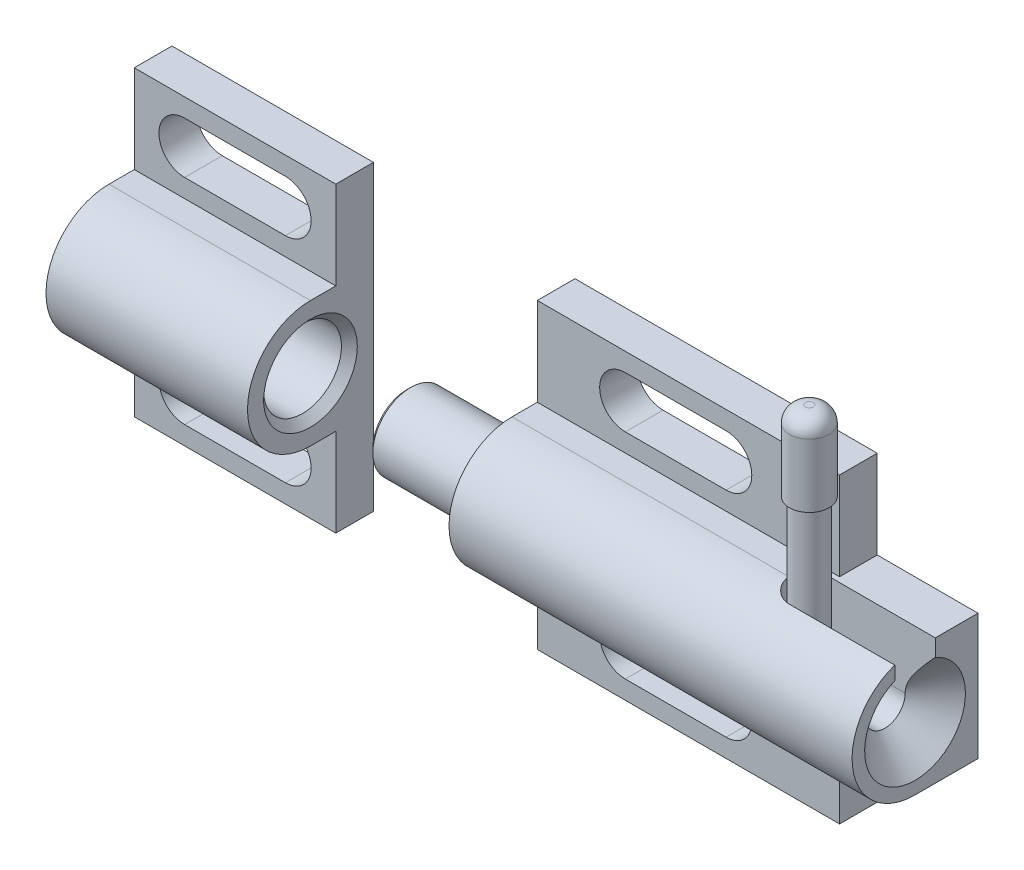
SolidWorks part; units mm, degrees
ref_plane "Front Plane" through (0, 0, 0) normal (0, 0, 1) x (1, 0, 0)
ref_plane "Top Plane" through (0, 0, 0) normal (0, 1, 0) x (1, 0, 0)
ref_plane "Right Plane" through (0, 0, 0) normal (1, 0, 0) x (0, 0, -1)
sketch "Sketch1" plane through (0, 0, 0) normal (1, 0, 0) x (0, 0, -1)
  line L0 (0, -19.05) -> (0, 19.05)
  line L3 (-4.7498, -19.05) -> (-4.7498, -7.9375)
  line L4 (-4.7498, 19.05) -> (0, 19.05)
  line L5 (0, -19.05) -> (-4.7498, -19.05)
  line L16 (-4.7498, 7.9375) -> (-4.7498, 19.05)
  line L17 (0, 0) -> (-15.875, 0) construction
  line L18 (-7.9375, 7.9375) -> (-4.7498, 7.9375)
  line L19 (-7.9375, -7.9375) -> (-4.7498, -7.9375)
  arc A10 (-7.9375, 7.9375) -> (-7.9375, -7.9375) centre (-7.9375, 0) ccw
  circle A12 centre (-7.9375, 0) radius 7.9375 construction
  dimension "D1" = 38.1
  dimension "D2" = 15.875
  dimension "D3" = 4.7498
extrude "Boss-Extrude1" add sketch "Sketch1" against normal blind 25.4
sketch "Sketch2" plane through (0, 0, 0) normal (0, 1, 0) x (1, 0, 0)
  line L0 (0, -7.9375) -> (-25.4, -7.9375) construction
  line L1 (-25.4, -7.9375) -> (-25.4, -15.875) construction
  line L2 (-25.4, -7.9375) -> (-25.4, -10.4902)
  line L3 (-25.4, -10.4902) -> (-19.05, -10.4902)
  line L4 (-19.05, -10.4902) -> (-19.05, -12.8397)
  line L5 (-19.05, -12.8397) -> (-1, -12.8397)
  line L6 (-1, -12.8397) -> (0, -13.8397)
  line L7 (0, -13.8397) -> (0, -7.9375)
  line L8 (0, -7.9375) -> (-25.4, -7.9375)
  dimension "D1" = 5.1054
  dimension "D2" = 9.8044
  dimension "D3" = 19.05
  dimension "D4" = 1
  dimension "D5" = 45
revolve "Cut-Revolve1" cut sketch "Sketch2" angle 360 about L0
sketch "Sketch3" plane through (0, 0, 0) normal (0, 0, 1) x (1, 0, 0)
  line L0 (-19.05, 13.4874) -> (-6.35, 13.4874) construction
  line L1 (-19.05, 16.7259) -> (-6.35, 16.7259)
  line L2 (-19.05, 10.2489) -> (-6.35, 10.2489)
  line L3 (-25.4, 0) -> (0, 0) construction
  line L4 (-25.4, -19.05) -> (-25.4, 19.05) construction
  line L5 (-19.05, -13.4874) -> (-6.35, -13.4874) construction
  line L6 (-19.05, -16.7259) -> (-6.35, -16.7259)
  line L7 (-19.05, -10.2489) -> (-6.35, -10.2489)
  line L8 (-12.7, 13.4874) -> (-12.7, 0) construction
  arc A0 (-19.05, 16.7259) -> (-19.05, 10.2489) centre (-19.05, 13.4874) ccw
  arc A1 (-6.35, 10.2489) -> (-6.35, 16.7259) centre (-6.35, 13.4874) ccw
  arc A2 (-19.05, -16.7259) -> (-19.05, -10.2489) centre (-19.05, -13.4874) cw
  arc A3 (-6.35, -10.2489) -> (-6.35, -16.7259) centre (-6.35, -13.4874) cw
  point P2 (-12.7, 13.4874)
  point P14 (-12.7, -13.4874)
  dimension "D1" = 26.9748
  dimension "D2" = 6.477
  dimension "D3" = 12.7
extrude "Cut-Extrude2" cut sketch "Sketch3" along normal up to next
ref_plane "Plane1" through (25.4, 0, 0) normal (1, 0, 0) x (0, 0, -1)
sketch "Sketch4" plane through (25.4, 0, 0) normal (1, 0, 0) x (0, 0, -1)
  line L7 (0, -19.05) -> (0, 19.05)
  line L8 (0, 19.05) -> (-4.7498, 19.05)
  line L9 (-4.7498, 19.05) -> (-4.7498, 7.9375)
  line L10 (-4.7498, 7.9375) -> (-7.9375, 7.9375)
  line L11 (-7.9375, -7.9375) -> (-4.7498, -7.9375)
  line L12 (-4.7498, -7.9375) -> (-4.7498, -19.05)
  line L13 (-4.7498, -19.05) -> (0, -19.05)
  line L14 (0, -19.05) -> (0, 19.05)
  line L15 (0, 19.05) -> (-4.7498, 19.05)
  line L16 (-4.7498, 19.05) -> (-4.7498, 7.9375)
  line L17 (-4.7498, 7.9375) -> (-7.9375, 7.9375)
  line L18 (-7.9375, -7.9375) -> (-4.7498, -7.9375)
  line L19 (-4.7498, -7.9375) -> (-4.7498, -19.05)
  line L20 (-4.7498, -19.05) -> (0, -19.05)
  arc A1 (-7.9375, 7.9375) -> (-7.9375, -7.9375) centre (-7.9375, 0) ccw
  arc A2 (-7.9375, 7.9375) -> (-7.9375, -7.9375) centre (-7.9375, 0) ccw
  dimension "D1" = 0
extrude "Boss-Extrude2" add sketch "Sketch4" along normal blind 50.8 separate body
sketch "Sketch5" plane through (76.2, 0, 0) normal (1, 0, 0) x (0, 0, -1)
  line L1 (0, 19.05) -> (-4.7498, 19.05)
  line L2 (0, 19.05) -> (0, 7.9375)
  line L3 (0, 7.9375) -> (-4.7498, 7.9375)
  line L4 (-4.7498, 19.05) -> (-4.7498, 7.9375)
  line L5 (0, -19.05) -> (-4.7498, -19.05)
  line L6 (0, -19.05) -> (0, -7.9375)
  line L7 (0, -7.9375) -> (-4.7498, -7.9375)
  line L8 (-4.7498, -19.05) -> (-4.7498, -7.9375)
extrude "Cut-Extrude3" cut sketch "Sketch5" against normal blind 12.7
sketch "Sketch6" plane through (0, 0, 0) normal (0, 1, 0) x (1, 0, 0)
  line L0 (25.4, -7.9375) -> (76.2, -7.9375) construction
  line L1 (76.2, -15.875) -> (76.2, -7.9375) construction
  line L2 (25.4, -7.9375) -> (25.4, -13.8397)
  line L3 (25.4, -7.9375) -> (25.4, -15.875) construction
  line L4 (25.4, -13.8397) -> (26.4, -12.8397)
  line L5 (26.4, -12.8397) -> (57.15, -12.8397)
  line L6 (57.15, -12.8397) -> (58.5617, -10.4902)
  line L7 (58.5617, -10.4902) -> (72.4027, -10.4902)
  line L8 (72.4027, -10.4902) -> (76.2, -14.2875)
  line L9 (76.2, -7.9375) -> (76.2, -14.2875)
  line L10 (25.4, -7.9375) -> (76.2, -7.9375)
  dimension "D1" = 12.7
  dimension "D2" = 5.1054
  dimension "D3" = 45
  dimension "D4" = 59
  dimension "D5" = 9.8044
  dimension "D6" = 1
  dimension "D7" = 45
  dimension "D8" = 31.75
revolve "Cut-Revolve2" cut sketch "Sketch6" angle 360 about L0
sketch "Sketch7" plane through (0, 0, 0) normal (0, 1, 0) x (1, 0, 0)
  line L0 (76.2, -7.9375) -> (60.3225, -7.9375) construction
  line L1 (62.8752, -10.4902) -> (76.2, -10.4902)
  line L2 (76.2, -7.9375) -> (76.2, -14.2875) construction
  line L3 (58.5617, -10.4902) -> (72.4027, -10.4902) construction
  line L4 (25.4, -7.9375) -> (76.2, -7.9375) construction
  line L5 (62.8752, -5.3848) -> (76.2, -5.3848)
  line L6 (76.2, -5.3848) -> (76.2, -10.4902)
  arc A0 (62.8752, -5.3848) -> (62.8752, -10.4902) centre (62.8752, -7.9375) ccw
  dimension "D1" = 15.8775
extrude "Cut-Extrude4" cut sketch "Sketch7" along normal up to next (7.9375 mm away)
sketch "Sketch8" plane through (0, 0, 0) normal (0, 0, 1) x (1, 0, 0)
  line L0 (36.4998, 13.4874) -> (49.1998, 13.4874) construction
  line L1 (36.4998, 16.7259) -> (49.1998, 16.7259)
  line L2 (36.4998, 10.2489) -> (49.1998, 10.2489)
  line L3 (25.4, 0) -> (76.2, 0) construction
  line L4 (76.2, -7.9375) -> (76.2, 7.9375) construction
  line L5 (36.4998, -13.4874) -> (49.1998, -13.4874) construction
  line L6 (36.4998, -16.7259) -> (49.1998, -16.7259)
  line L7 (36.4998, -10.2489) -> (49.1998, -10.2489)
  line L9 (63.5, 19.05) -> (63.5, 7.9375) construction
  arc A0 (36.4998, 16.7259) -> (36.4998, 10.2489) centre (36.4998, 13.4874) ccw
  arc A1 (49.1998, 10.2489) -> (49.1998, 16.7259) centre (49.1998, 13.4874) ccw
  arc A2 (36.4998, -16.7259) -> (36.4998, -10.2489) centre (36.4998, -13.4874) cw
  arc A3 (49.1998, -10.2489) -> (49.1998, -16.7259) centre (49.1998, -13.4874) cw
  point P2 (42.8498, 13.4874)
  point P14 (42.8498, -13.4874)
  dimension "D1" = 6.477
  dimension "D2" = 12.7
  dimension "D3" = 14.3002
  dimension "D4" = 26.9748
  dimension "D5" = 11.0998
extrude "Cut-Extrude5" cut sketch "Sketch8" along normal up to next (4.7498 mm away)
ref_plane "Plane2" through (0, 0, 7.9375) normal (0, 0, 1) x (1, 0, 0)
sketch "Sketch9" plane through (0, 0, 7.9375) normal (0, 0, 1) x (1, 0, 0)
  line L0 (12.1252, 0) -> (60.3752, 0) construction
  line L1 (62.8752, 2.5) -> (62.8752, 28) construction
  line L2 (60.8752, 28) -> (64.8752, 28) construction
  line L3 (12.1252, 0) -> (12.1252, 4.2625)
  line L4 (12.1252, 4.2625) -> (12.6252, 4.7625)
  line L5 (12.6252, 4.7625) -> (41.6252, 4.7625)
  line L6 (41.6252, 4.7625) -> (41.6252, 2)
  line L7 (41.6252, 2) -> (60.3752, 2)
  line L8 (60.3752, 2) -> (60.3752, 0)
  line L9 (41.6252, 2) -> (41.6252, -2) construction
  line L10 (12.1252, 0) -> (60.3752, 0)
  line L11 (25.4, 7.9375) -> (25.4, -7.9375) construction
  arc A0 (60.3752, 0) -> (62.8752, 2.5) centre (60.3752, 2.5) ccw construction
  point P3 (41.6252, 0)
  point P10 (62.8752, 0)
  dimension "D5" = 2.5
  dimension "D1" = 50.75
  dimension "D2" = 28
  dimension "D3" = 29.5
  dimension "D4" = 4
  dimension "D6" = 9.525
  dimension "D7" = 0.5
  dimension "D8" = 45
  dimension "D9" = 13.2748
revolve "Revolve1" add sketch "Sketch9" angle 360 about L10
sketch "Sketch11" plane through (0, 0, 7.9375) normal (0, 0, 1) x (1, 0, 0)
  line L0 (60.8752, 2.5) -> (60.8752, 18)
  line L1 (60.8752, 2.5) -> (62.8752, 2.5)
  line L2 (62.8752, 28) -> (62.3752, 28)
  line L3 (60.8752, 28) -> (64.8752, 28) construction
  line L4 (60.3752, 26) -> (60.3752, 18)
  line L5 (60.8752, 18) -> (60.3752, 18)
  line L6 (62.8752, 2.5) -> (62.8752, 28) construction
  line L7 (62.8752, 28) -> (62.8752, 2.5)
  arc A0 (62.3752, 28) -> (60.3752, 26) centre (62.3752, 26) ccw
  dimension "D3" = 2
  dimension "D1" = 5
  dimension "D2" = 10
revolve "Revolve2" add sketch "Sketch11" angle 360 about L6
sketch "Sketch12" plane through (60.3752, 0, 0) normal (1, 0, 0) x (0, 0, -1)
  circle A1 centre (-7.9375, 0) radius 2
  circle A2 centre (-7.9375, 0) radius 2
  dimension "D1" = 0
sketch "Sketch13" plane through (0, 0, 7.9375) normal (0, 0, 1) x (1, 0, 0)
  arc A0 (60.3752, 0) -> (62.8752, 2.5) centre (60.3752, 2.5) ccw construction
  arc A1 (60.3752, 0) -> (62.8752, 2.5) centre (60.3752, 2.5) ccw
sweep "Sweep1" add profiles "Sketch12" path "Sketch13"
